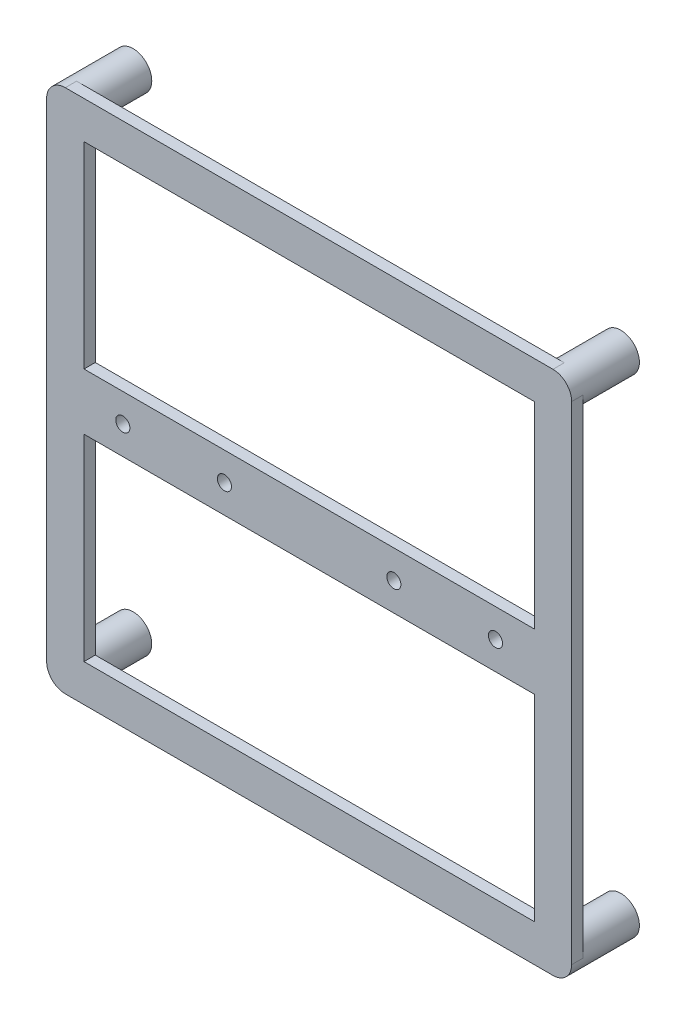
SolidWorks part; units mm, degrees
ref_plane "Ebene vorne" through (0, 0, 0) normal (0, 0, 1) x (1, 0, 0)
ref_plane "Ebene oben" through (0, 0, 0) normal (0, 1, 0) x (1, 0, 0)
ref_plane "Ebene rechts" through (0, 0, 0) normal (1, 0, 0) x (0, 0, -1)
sketch "Skizze2" plane through (0, 0, 0) normal (0, 0, 1) x (1, 0, 0)
  circle A0 centre (-43.18, 43.18) radius 1.25
  circle A1 centre (29.21, -5.08) radius 0.4
  circle A2 centre (29.21, -5.08) radius 0.4
  circle A3 centre (29.21, -15.24) radius 0.4
  circle A4 centre (29.21, -15.24) radius 0.4
  circle A5 centre (28, -10.16) radius 0.47
  circle A6 centre (28, -10.16) radius 0.47
  circle A7 centre (26.426, 10.414) radius 0.4
  circle A8 centre (26.426, 10.414) radius 0.4
  circle A9 centre (26.426, 18.034) radius 0.4
  circle A10 centre (26.426, 18.034) radius 0.4
  circle A11 centre (25.4, -27.94) radius 0.8
  circle A12 centre (25.4, -27.94) radius 0.8
  circle A13 centre (29.21, -33.02) radius 0.8
  circle A14 centre (29.21, -33.02) radius 0.8
  circle A15 centre (-43.18, 43.18) radius 3.3118
  circle A16 centre (-43.18, 43.18) radius 3.3118
  circle A17 centre (43.18, 43.18) radius 3.302
  circle A18 centre (43.18, 43.18) radius 3.302
  circle A19 centre (43.18, -43.18) radius 3.302
  circle A20 centre (43.18, -43.18) radius 3.302
  circle A21 centre (18.542, 22.86) radius 0.5
  circle A22 centre (18.542, 22.86) radius 0.5
  circle A23 centre (2.54, -27.94) radius 0.8
  circle A24 centre (2.54, -27.94) radius 0.8
  circle A25 centre (6.35, -27.94) radius 0.8
  circle A26 centre (6.35, -27.94) radius 0.8
  circle A27 centre (6.35, -15.24) radius 0.4
  circle A28 centre (6.35, -15.24) radius 0.4
  circle A29 centre (21.59, -15.24) radius 0.4
  circle A30 centre (21.59, -15.24) radius 0.4
  circle A31 centre (12.7, 32.766) radius 0.75
  circle A32 centre (12.7, 32.766) radius 0.75
  circle A33 centre (22.86, 31.068) radius 0.4
  circle A34 centre (22.86, 31.068) radius 0.4
  circle A35 centre (15.24, 36.068) radius 0.645
  circle A36 centre (15.24, 36.068) radius 0.645
  circle A37 centre (10.16, 36.068) radius 0.645
  circle A38 centre (10.16, 36.068) radius 0.645
  circle A39 centre (12.7, 36.068) radius 0.645
  circle A40 centre (12.7, 36.068) radius 0.645
  circle A41 centre (22.86, 36.068) radius 0.4
  circle A42 centre (22.86, 36.068) radius 0.4
  circle A43 centre (25.4, -33.02) radius 0.8
  circle A44 centre (25.4, -33.02) radius 0.8
  circle A45 centre (6.35, -33.02) radius 0.8
  circle A46 centre (6.35, -33.02) radius 0.8
  circle A47 centre (2.54, -33.02) radius 0.8
  circle A48 centre (2.54, -33.02) radius 0.8
  circle A49 centre (35.56, 33.274) radius 0.8
  circle A50 centre (35.56, 33.274) radius 0.8
  circle A51 centre (31.75, 33.274) radius 0.8
  circle A52 centre (31.75, 33.274) radius 0.8
  circle A53 centre (31.75, 28.194) radius 0.8
  circle A54 centre (31.75, 28.194) radius 0.8
  circle A55 centre (35.56, 28.194) radius 0.8
  circle A56 centre (35.56, 28.194) radius 0.8
  circle A57 centre (29.21, -27.94) radius 0.8
  circle A58 centre (29.21, -27.94) radius 0.8
  circle A59 centre (-28.194, -1.27) radius 0.8
  circle A60 centre (-28.194, -1.27) radius 0.8
  circle A61 centre (-33.274, -1.27) radius 0.8
  circle A62 centre (-33.274, -1.27) radius 0.8
  circle A63 centre (-33.274, 2.54) radius 0.8
  circle A64 centre (-33.274, 2.54) radius 0.8
  circle A65 centre (-28.194, -5.08) radius 0.8
  circle A66 centre (-28.194, -5.08) radius 0.8
  circle A67 centre (-33.274, -5.08) radius 0.8
  circle A68 centre (-33.274, -5.08) radius 0.8
  circle A69 centre (-28.194, -8.89) radius 0.8
  circle A70 centre (-28.194, -8.89) radius 0.8
  circle A71 centre (-33.274, -8.89) radius 0.8
  circle A72 centre (-33.274, -8.89) radius 0.8
  circle A73 centre (-43.18, -43.18) radius 3.302
  circle A74 centre (-43.18, -43.18) radius 3.302
  circle A75 centre (-30.48, -33.02) radius 0.8
  circle A76 centre (-30.48, -33.02) radius 0.8
  circle A77 centre (-34.29, -33.02) radius 0.8
  circle A78 centre (-34.29, -33.02) radius 0.8
  circle A79 centre (-30.48, -27.94) radius 0.8
  circle A80 centre (-30.48, -27.94) radius 0.8
  circle A81 centre (-34.29, -27.94) radius 0.8
  circle A82 centre (-34.29, -27.94) radius 0.8
  circle A83 centre (-26.67, -33.02) radius 0.8
  circle A84 centre (-26.67, -33.02) radius 0.8
  circle A85 centre (-26.67, -27.94) radius 0.8
  circle A86 centre (-26.67, -27.94) radius 0.8
  circle A87 centre (-22.86, -33.02) radius 0.8
  circle A88 centre (-22.86, -33.02) radius 0.8
  circle A89 centre (-22.86, -27.94) radius 0.8
  circle A90 centre (-22.86, -27.94) radius 0.8
  circle A91 centre (-16.51, -33.02) radius 0.8
  circle A92 centre (-16.51, -33.02) radius 0.8
  circle A93 centre (0, 18.098) radius 0.3665
  circle A94 centre (0, 18.098) radius 0.3665
  circle A95 centre (-2.54, 18.098) radius 0.3665
  circle A96 centre (-2.54, 18.098) radius 0.3665
  circle A97 centre (-2.54, 10.16) radius 0.3665
  circle A98 centre (-2.54, 10.16) radius 0.3665
  circle A99 centre (0, 10.16) radius 0.3665
  circle A100 centre (0, 10.16) radius 0.3665
  circle A101 centre (-5.08, 10.16) radius 0.3665
  circle A102 centre (-5.08, 10.16) radius 0.3665
  circle A103 centre (-5.08, 18.098) radius 0.3665
  circle A104 centre (-5.08, 18.098) radius 0.3665
  circle A105 centre (-6.35, -7.62) radius 0.69
  circle A106 centre (-6.35, -7.62) radius 0.69
  circle A107 centre (-6.35, -5.08) radius 0.69
  circle A108 centre (-6.35, -5.08) radius 0.69
  circle A109 centre (-1.27, -5.08) radius 0.4
  circle A110 centre (-1.27, -5.08) radius 0.4
  circle A111 centre (-6.35, -2.54) radius 0.69
  circle A112 centre (-6.35, -2.54) radius 0.69
  circle A113 centre (-9.652, -5.08) radius 0.75
  circle A114 centre (-9.652, -5.08) radius 0.75
  circle A115 centre (-7.62, 10.16) radius 0.3665
  circle A116 centre (-7.62, 10.16) radius 0.3665
  circle A117 centre (-10.16, 10.16) radius 0.3665
  circle A118 centre (-10.16, 10.16) radius 0.3665
  circle A119 centre (-7.62, 18.098) radius 0.3665
  circle A120 centre (-7.62, 18.098) radius 0.3665
  circle A121 centre (-10.16, 18.098) radius 0.3665
  circle A122 centre (-10.16, 18.098) radius 0.3665
  circle A123 centre (-28.194, 16.51) radius 0.8
  circle A124 centre (-28.194, 16.51) radius 0.8
  circle A125 centre (-28.194, 10.16) radius 0.8
  circle A126 centre (-28.194, 10.16) radius 0.8
  circle A127 centre (-28.194, 6.35) radius 0.8
  circle A128 centre (-28.194, 6.35) radius 0.8
  circle A129 centre (-12.7, -27.94) radius 0.8
  circle A130 centre (-12.7, -27.94) radius 0.8
  circle A131 centre (-8.89, -27.94) radius 0.8
  circle A132 centre (-8.89, -27.94) radius 0.8
  circle A133 centre (-5.08, -27.94) radius 0.8
  circle A134 centre (-5.08, -27.94) radius 0.8
  circle A135 centre (-16.51, -27.94) radius 0.8
  circle A136 centre (-16.51, -27.94) radius 0.8
  circle A137 centre (-1.27, -15.24) radius 0.4
  circle A138 centre (-1.27, -15.24) radius 0.4
  circle A139 centre (-0.12, -10.16) radius 0.47
  circle A140 centre (-0.12, -10.16) radius 0.47
  circle A141 centre (-33.274, 16.51) radius 0.8
  circle A142 centre (-33.274, 16.51) radius 0.8
  circle A143 centre (-33.274, 6.35) radius 0.8
  circle A144 centre (-33.274, 6.35) radius 0.8
  circle A145 centre (-33.274, 10.16) radius 0.8
  circle A146 centre (-33.274, 10.16) radius 0.8
  circle A147 centre (-5.08, -33.02) radius 0.8
  circle A148 centre (-5.08, -33.02) radius 0.8
  circle A149 centre (-8.89, -33.02) radius 0.8
  circle A150 centre (-8.89, -33.02) radius 0.8
  circle A151 centre (-12.7, -33.02) radius 0.8
  circle A152 centre (-12.7, -33.02) radius 0.8
  circle A153 centre (-28.194, 35.56) radius 0.8
  circle A154 centre (-28.194, 35.56) radius 0.8
  circle A155 centre (-33.274, 35.56) radius 0.8
  circle A156 centre (-33.274, 35.56) radius 0.8
  circle A157 centre (-33.274, 31.75) radius 0.8
  circle A158 centre (-33.274, 31.75) radius 0.8
  circle A159 centre (-28.194, 31.75) radius 0.8
  circle A160 centre (-28.194, 31.75) radius 0.8
  circle A161 centre (-33.274, 24.13) radius 0.8
  circle A162 centre (-33.274, 24.13) radius 0.8
  circle A163 centre (-28.194, 24.13) radius 0.8
  circle A164 centre (-28.194, 24.13) radius 0.8
  circle A165 centre (-28.194, 27.94) radius 0.8
  circle A166 centre (-28.194, 27.94) radius 0.8
  circle A167 centre (-33.274, 27.94) radius 0.8
  circle A168 centre (-33.274, 27.94) radius 0.8
  circle A169 centre (-8.382, 36.068) radius 0.4
  circle A170 centre (-8.382, 36.068) radius 0.4
  circle A171 centre (-8.382, 28.448) radius 0.4
  circle A172 centre (-8.382, 28.448) radius 0.4
  circle A173 centre (-28.194, 20.32) radius 0.8
  circle A174 centre (-28.194, 20.32) radius 0.8
  circle A175 centre (-33.274, 20.32) radius 0.8
  circle A176 centre (-33.274, 20.32) radius 0.8
  circle A177 centre (0, 34.036) radius 0.4
  circle A178 centre (0, 34.036) radius 0.4
  circle A179 centre (-0.04, 30.4) radius 0.45
  circle A180 centre (-0.04, 30.4) radius 0.45
  circle A181 centre (-2.54, 25.4) radius 0.45
  circle A182 centre (-2.54, 25.4) radius 0.45
  circle A183 centre (0, 36.036) radius 0.4
  circle A184 centre (0, 36.036) radius 0.4
  circle A185 centre (25.4, -10.16) radius 0.47
  circle A186 centre (25.4, -10.16) radius 0.47
  circle A187 centre (25.41, 6.424) radius 0.4
  circle A188 centre (25.41, 6.424) radius 0.4
  circle A189 centre (25.41, -1.196) radius 0.4
  circle A190 centre (25.41, -1.196) radius 0.4
  circle A191 centre (16.51, -7.62) radius 0.69
  circle A192 centre (16.51, -7.62) radius 0.69
  circle A193 centre (22.8, -10.16) radius 0.47
  circle A194 centre (22.8, -10.16) radius 0.47
  circle A195 centre (21.59, -5.08) radius 0.4
  circle A196 centre (21.59, -5.08) radius 0.4
  circle A197 centre (10.16, 18.098) radius 0.3665
  circle A198 centre (10.16, 18.098) radius 0.3665
  circle A199 centre (17.78, 18.098) radius 0.3665
  circle A200 centre (17.78, 18.098) radius 0.3665
  circle A201 centre (15.24, 18.098) radius 0.3665
  circle A202 centre (15.24, 18.098) radius 0.3665
  circle A203 centre (15.24, 10.16) radius 0.3665
  circle A204 centre (15.24, 10.16) radius 0.3665
  circle A205 centre (17.78, 10.16) radius 0.3665
  circle A206 centre (17.78, 10.16) radius 0.3665
  circle A207 centre (22.86, 10.16) radius 0.3665
  circle A208 centre (22.86, 10.16) radius 0.3665
  circle A209 centre (22.86, 18.098) radius 0.3665
  circle A210 centre (22.86, 18.098) radius 0.3665
  circle A211 centre (20.32, 18.098) radius 0.3665
  circle A212 centre (20.32, 18.098) radius 0.3665
  circle A213 centre (20.32, 10.16) radius 0.3665
  circle A214 centre (20.32, 10.16) radius 0.3665
  circle A215 centre (2.48, -10.16) radius 0.47
  circle A216 centre (2.48, -10.16) radius 0.47
  circle A217 centre (5.08, -10.16) radius 0.47
  circle A218 centre (5.08, -10.16) radius 0.47
  circle A219 centre (2.46, 25.4) radius 0.45
  circle A220 centre (2.46, 25.4) radius 0.45
  circle A221 centre (2.54, 18.098) radius 0.3665
  circle A222 centre (2.54, 18.098) radius 0.3665
  circle A223 centre (2.54, 10.16) radius 0.3665
  circle A224 centre (2.54, 10.16) radius 0.3665
  circle A225 centre (5.08, 10.16) radius 0.3665
  circle A226 centre (5.08, 10.16) radius 0.3665
  circle A227 centre (5.08, 18.098) radius 0.3665
  circle A228 centre (5.08, 18.098) radius 0.3665
  circle A229 centre (6.35, -5.08) radius 0.4
  circle A230 centre (6.35, -5.08) radius 0.4
  circle A231 centre (2.55, -1.196) radius 0.4
  circle A232 centre (2.55, -1.196) radius 0.4
  circle A233 centre (2.55, 6.424) radius 0.4
  circle A234 centre (2.55, 6.424) radius 0.4
  circle A235 centre (13.462, 22.86) radius 0.5
  circle A236 centre (13.462, 22.86) radius 0.5
  circle A237 centre (12.7, 18.098) radius 0.3665
  circle A238 centre (12.7, 18.098) radius 0.3665
  circle A239 centre (7.62, 18.098) radius 0.3665
  circle A240 centre (7.62, 18.098) radius 0.3665
  circle A241 centre (7.62, 10.16) radius 0.3665
  circle A242 centre (7.62, 10.16) radius 0.3665
  circle A243 centre (10.16, 10.16) radius 0.3665
  circle A244 centre (10.16, 10.16) radius 0.3665
  circle A245 centre (12.7, 10.16) radius 0.3665
  circle A246 centre (12.7, 10.16) radius 0.3665
  circle A247 centre (13.462, 25.4) radius 0.5
  circle A248 centre (13.462, 25.4) radius 0.5
  circle A249 centre (13.208, -5.08) radius 0.75
  circle A250 centre (13.208, -5.08) radius 0.75
  circle A251 centre (16.002, 22.86) radius 0.5
  circle A252 centre (16.002, 22.86) radius 0.5
  circle A253 centre (16.002, 25.4) radius 0.5
  circle A254 centre (16.002, 25.4) radius 0.5
  circle A255 centre (16.51, -2.54) radius 0.69
  circle A256 centre (16.51, -2.54) radius 0.69
  circle A257 centre (16.51, -5.08) radius 0.69
  circle A258 centre (16.51, -5.08) radius 0.69
  circle A259 centre (18.542, 25.4) radius 0.5
  circle A260 centre (18.542, 25.4) radius 0.5
  circle A261 centre (-28.194, 2.54) radius 0.8
  circle A262 centre (-28.194, 2.54) radius 0.8
  circle A263 centre (43.18, 43.18) radius 1.25
  circle A264 centre (43.18, -43.18) radius 1.25
  circle A265 centre (-43.18, -43.18) radius 1.25
  dimension "D132" = 2.5
  dimension "D1" = 0
  dimension "D2" = 0
  dimension "D3" = 0
  dimension "D4" = 0
  dimension "D5" = 0
  dimension "D6" = 0
  dimension "D7" = 0
  dimension "D8" = 0
  dimension "D9" = 0
  dimension "D10" = 0
  dimension "D11" = 0
  dimension "D12" = 0
  dimension "D13" = 0
  dimension "D14" = 0
  dimension "D15" = 0
  dimension "D16" = 0
  dimension "D17" = 0
  dimension "D18" = 0
  dimension "D19" = 0
  dimension "D20" = 0
  dimension "D21" = 0
  dimension "D22" = 0
  dimension "D23" = 0
  dimension "D24" = 0
  dimension "D25" = 0
  dimension "D26" = 0
  dimension "D27" = 0
  dimension "D28" = 0
  dimension "D29" = 0
  dimension "D30" = 0
  dimension "D31" = 0
  dimension "D32" = 0
  dimension "D33" = 0
  dimension "D34" = 0
  dimension "D35" = 0
  dimension "D36" = 0
  dimension "D37" = 0
  dimension "D38" = 0
  dimension "D39" = 0
  dimension "D40" = 0
  dimension "D41" = 0
  dimension "D42" = 0
  dimension "D43" = 0
  dimension "D44" = 0
  dimension "D45" = 0
  dimension "D46" = 0
  dimension "D47" = 0
  dimension "D48" = 0
  dimension "D49" = 0
  dimension "D50" = 0
  dimension "D51" = 0
  dimension "D52" = 0
  dimension "D53" = 0
  dimension "D54" = 0
  dimension "D55" = 0
  dimension "D56" = 0
  dimension "D57" = 0
  dimension "D58" = 0
  dimension "D59" = 0
  dimension "D60" = 0
  dimension "D61" = 0
  dimension "D62" = 0
  dimension "D63" = 0
  dimension "D64" = 0
  dimension "D65" = 0
  dimension "D66" = 0
  dimension "D67" = 0
  dimension "D68" = 0
  dimension "D69" = 0
  dimension "D70" = 0
  dimension "D71" = 0
  dimension "D72" = 0
  dimension "D73" = 0
  dimension "D74" = 0
  dimension "D75" = 0
  dimension "D76" = 0
  dimension "D77" = 0
  dimension "D78" = 0
  dimension "D79" = 0
  dimension "D80" = 0
  dimension "D81" = 0
  dimension "D82" = 0
  dimension "D83" = 0
  dimension "D84" = 0
  dimension "D85" = 0
  dimension "D86" = 0
  dimension "D87" = 0
  dimension "D88" = 0
  dimension "D89" = 0
  dimension "D90" = 0
  dimension "D91" = 0
  dimension "D92" = 0
  dimension "D93" = 0
  dimension "D94" = 0
  dimension "D95" = 0
  dimension "D96" = 0
  dimension "D97" = 0
  dimension "D98" = 0
  dimension "D99" = 0
  dimension "D100" = 0
  dimension "D101" = 0
  dimension "D102" = 0
  dimension "D103" = 0
  dimension "D104" = 0
  dimension "D105" = 0
  dimension "D106" = 0
  dimension "D107" = 0
  dimension "D108" = 0
  dimension "D109" = 0
  dimension "D110" = 0
  dimension "D111" = 0
  dimension "D112" = 0
  dimension "D113" = 0
  dimension "D114" = 0
  dimension "D115" = 0
  dimension "D116" = 0
  dimension "D117" = 0
  dimension "D118" = 0
  dimension "D119" = 0
  dimension "D120" = 0
  dimension "D121" = 0
  dimension "D122" = 0
  dimension "D123" = 0
  dimension "D124" = 0
  dimension "D125" = 0
  dimension "D126" = 0
  dimension "D127" = 0
  dimension "D128" = 0
  dimension "D129" = 0
  dimension "D130" = 0
  dimension "D131" = 0
extrude "Aufsatz-Linear austragen1" add sketch "Skizze2" along normal blind 10 contours A16 A0 | A74 A265 | A20 A264 | A18 A263
sketch "Skizze3" plane through (0, 0, 10) normal (0, 0, 1) x (1, 0, 0)
  line L0 (-46.4918, 43.18) -> (-46.482, -43.18)
  line L1 (-43.18, -46.482) -> (43.18, -46.482)
  line L2 (46.482, -43.18) -> (46.482, 43.18)
  line L3 (-39.8731, -0.0002) -> (-39.8726, 4.9998)
  line L4 (43.18, 46.482) -> (-43.18, 46.4918)
  line L5 (-39.8682, 43.1796) -> (-39.878, -43.18)
  line L6 (-43.18, -39.878) -> (43.18, -39.878)
  line L7 (39.878, -43.18) -> (39.878, 43.18)
  line L8 (43.18, 39.878) -> (-43.18, 39.8682)
  line L9 (-39.8726, 4.9998) -> (39.878, 4.9998)
  line L10 (-39.8731, -0.0002) -> (-39.8737, -5.0002)
  line L11 (-39.8737, -5.0002) -> (39.878, -5.0002)
  line L12 (39.878, -5.0002) -> (39.878, 4.9998)
  circle A0 centre (-43.18, -43.18) radius 3.302 construction
  circle A1 centre (-43.18, -43.18) radius 3.302 construction
  circle A2 centre (43.18, -43.18) radius 3.302 construction
  circle A3 centre (43.18, -43.18) radius 3.302 construction
  circle A4 centre (43.18, 43.18) radius 3.302 construction
  circle A5 centre (43.18, 43.18) radius 3.302 construction
  circle A6 centre (-43.18, 43.18) radius 3.3118 construction
  circle A7 centre (-43.18, 43.18) radius 3.3118 construction
  circle A9 centre (-43.18, 43.18) radius 3.3118
  circle A10 centre (-43.18, 43.18) radius 3.3118
  circle A11 centre (43.18, 43.18) radius 3.302
  circle A12 centre (43.18, 43.18) radius 3.302
  circle A13 centre (43.18, -43.18) radius 3.302
  circle A14 centre (43.18, -43.18) radius 3.302
  circle A15 centre (-43.18, -43.18) radius 3.302
  circle A16 centre (-43.18, -43.18) radius 3.302
  circle M11 centre (-43.18, 43.18) radius 1.25
  circle M12 centre (-43.18, 43.18) radius 3.3118
  dimension "D1" = 5
  dimension "D2" = 5
  dimension "D3" = 0
  dimension "D4" = 0
  dimension "D5" = 0
  dimension "D6" = 0
extrude "Aufsatz-Linear austragen2" add sketch "Skizze3" along normal blind 2 contours L5 L11 L7 L9 L3 | A16 L6 L5 L3 L8 L0 M12 | A16 L1 A14 L7 L6 L5 | A14 L2 A12 L8 L7 L6 | A12 L4 L5 L8 L7 M12 | A16 L5 L6 | A16 | A14 L6 L7 | A14 | A12 L7 L8 | A12 | L8 L5 M12 | M12 M11 | M11
sketch "Skizze4" plane through (0, 0, 12) normal (0, 0, 1) x (1, 0, 0)
  line L2 (0, 0) -> (0.0027, 4.9998)
  line L3 (-39.8726, 4.9998) -> (39.878, 4.9998) construction
  circle A0 centre (-33, 0) radius 1.25
  circle A1 centre (-15, 0) radius 1.25
  circle A2 centre (15, -0.0163) radius 1.25
  circle A3 centre (33, -0.0359) radius 1.25
  dimension "D1" = 2.5
  dimension "D2" = 18
  dimension "D3" = 15
extrude "Schnitt-Linear austragen1" cut sketch "Skizze4" against normal blind 2 contours A0 | A1 | A3 | A2
